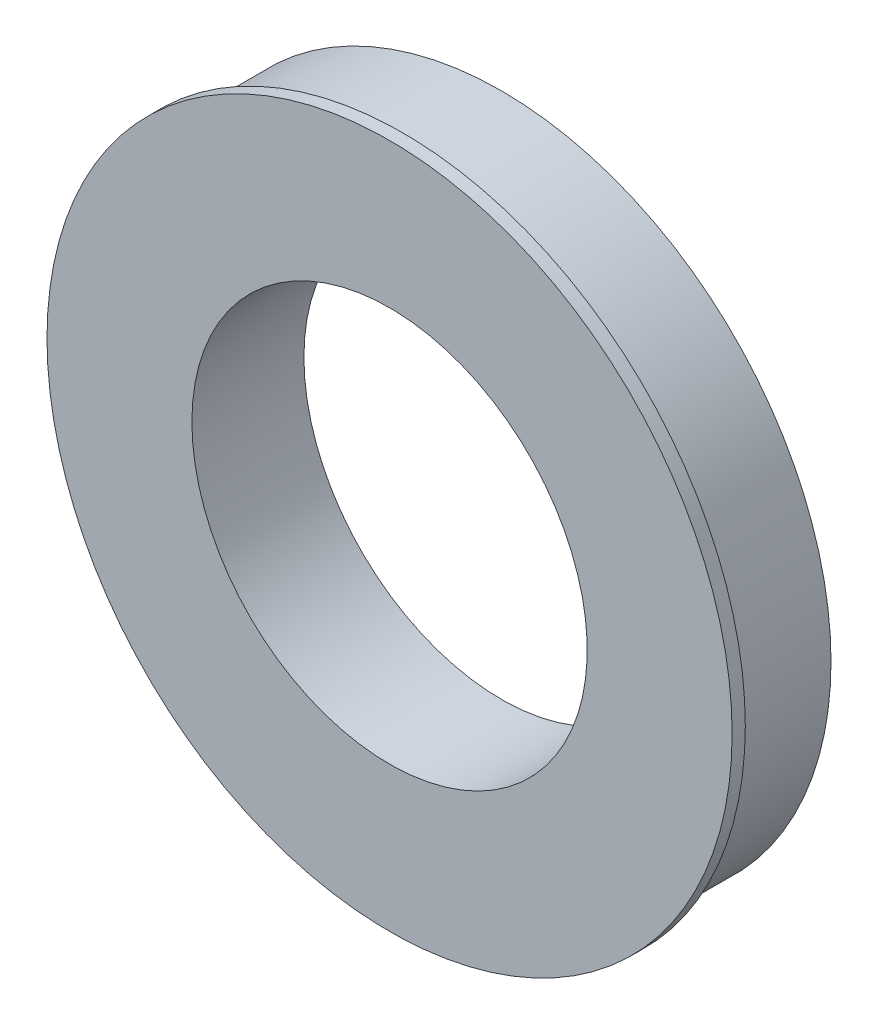
SolidWorks part; units mm, degrees
material "Alloy Steel"
ref_plane "Front Plane" through (0, 0, 0) normal (0, 0, 1) x (1, 0, 0)
ref_plane "Top Plane" through (0, 0, 0) normal (0, 1, 0) x (1, 0, 0)
ref_plane "Right Plane" through (0, 0, 0) normal (1, 0, 0) x (0, 0, -1)
sketch "Sketch1" plane through (0, 0, 0) normal (0, 0, 1) x (1, 0, 0)
  circle A0 centre (0, 0) radius 38.1
  circle A1 centre (0, 0) radius 63.5
  dimension "D1" = 127
  dimension "D2" = 76.2
extrude "Boss-Extrude1" add sketch "Sketch1" along normal blind 19.05
sketch "Sketch2" plane through (0, 0, 19.05) normal (0, 0, 1) x (1, 0, 0)
  circle A0 centre (0, 0) radius 38.1 construction
  circle A1 centre (0, 0) radius 38.1
  circle A2 centre (0, 0) radius 66.03
  dimension "D1" = 132.06
extrude "Boss-Extrude2" add sketch "Sketch2" along normal blind 2.54
